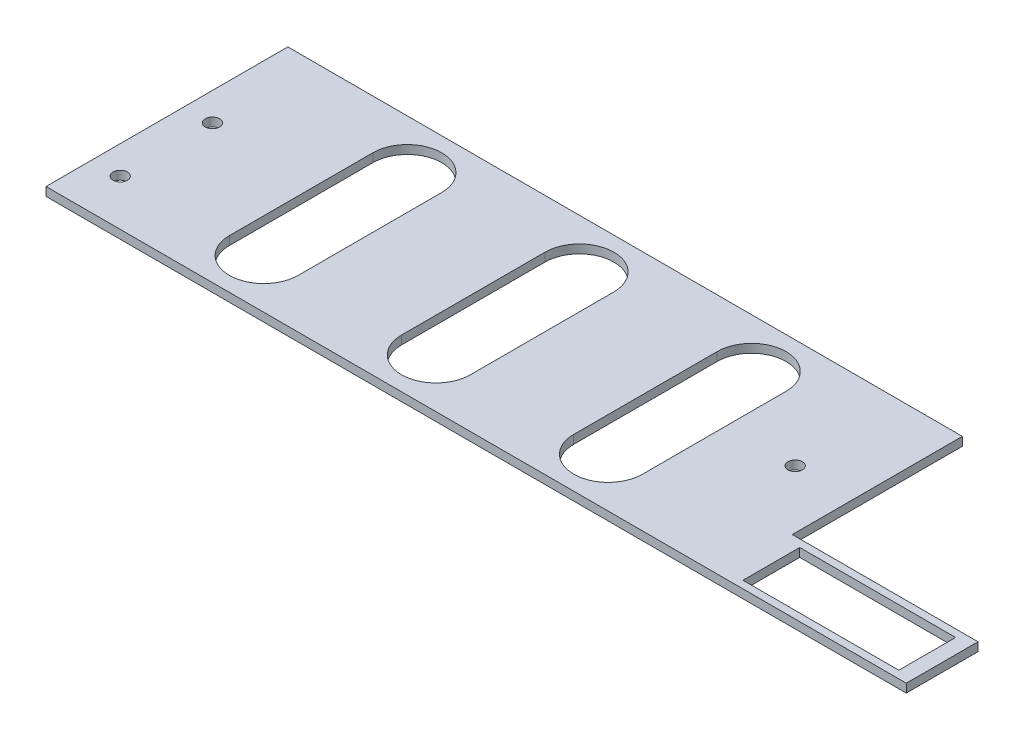
SolidWorks part; units mm, degrees
material "Custom Plastic"
ref_plane "Plan de face" through (0, 0, 0) normal (0, 0, 1) x (1, 0, 0)
ref_plane "Plan de dessus" through (0, 0, 0) normal (0, 1, 0) x (1, 0, 0)
ref_plane "Plan de droite" through (0, 0, 0) normal (1, 0, 0) x (0, 0, -1)
sketch "Esquisse1" plane through (0, 0, 0) normal (0, 1, 0) x (1, 0, 0)
  line L1 (-161.1743, 28.77) -> (138.6257, 28.77) construction
  line L2 (-161.1743, 28.77) -> (-161.1743, -35.5) construction
  line L3 (-161.1743, -35.5) -> (138.6257, -35.5) construction
  line L4 (138.6257, 28.77) -> (138.6257, -35.5) construction
  line L5 (-161.1743, 28.77) -> (138.6257, -35.5) construction
  line L6 (-161.1743, -35.5) -> (138.6257, 28.77) construction
  line L7 (138.6257, 18.77) -> (138.6257, -25.5) construction
  line L9 (-161.1743, 18.77) -> (-161.1743, -25.5)
  line L10 (-161.1743, 18.77) -> (-151.1743, 18.77) construction
  line L12 (-161.1743, -35.5) -> (138.6257, -35.5)
  line L13 (114.2615, -15.6877) -> (114.2615, -18.6342)
  line L14 (-151.1743, 28.77) -> (-151.1743, 18.77) construction
  line L15 (73.912, -0.4751) -> (73.912, -50000.4751) construction
  line L16 (-161.1743, -25.5) -> (-151.1743, -25.5) construction
  line L17 (-151.1743, -25.5) -> (-151.1743, -35.5) construction
  line L18 (67.162, 10.7475) -> (67.162, 2.8892) construction
  line L19 (-161.1743, 18.77) -> (138.6257, 18.77) construction
  line L20 (73.912, 28.77) -> (73.912, -10.5)
  line L21 (138.6257, -25.5) -> (-161.1743, -25.5) construction
  line L26 (114.2615, -15.6877) -> (79.1092, -15.6877)
  line L28 (-161.3743, 48.77) -> (-161.3743, -35.5) construction
  line L29 (114.2615, -15.6877) -> (114.2615, -32.887) construction
  line L30 (-161.1743, -25.5) -> (-161.1743, -35.5)
  line L33 (-161.1743, 28.77) -> (-161.1743, 18.77)
  line L34 (-161.1743, 28.77) -> (73.912, 28.77)
  line L36 (73.912, -10.5) -> (138.6257, -10.5)
  line L37 (138.6257, -10.5) -> (138.6257, -35.5)
  line L38 (114.2615, -32.887) -> (79.1092, -32.887)
  line L39 (138.6257, -35.5) -> (-161.3743, -35.5) construction
  line L40 (79.1092, -15.6877) -> (79.1092, -32.887)
  line L41 (114.2615, -15.6877) -> (79.1092, -32.887) construction
  line L42 (114.2615, -32.887) -> (79.1092, -15.6877) construction
  line L43 (-161.1743, -35.5) -> (-161.3743, -35.5) construction
  line L44 (132.6257, -18.6342) -> (114.2615, -18.6342)
  line L45 (132.6257, -18.6342) -> (132.6257, -32.887)
  line L46 (132.6257, -32.887) -> (114.2615, -32.887)
  line L47 (138.6257, -10.5) -> (73.912, -10.5) construction
  line L48 (114.2615, -18.6342) -> (114.2615, -32.887) construction
  line L49 (132.6257, -18.6342) -> (114.2615, -32.887) construction
  line L50 (73.912, 48.995) -> (73.912, -7.5) construction
  line L51 (132.6257, -32.887) -> (114.2615, -18.6342) construction
  circle A17 centre (-151.3743, -19.4325) radius 2.5
  circle A18 centre (-151.3743, 12.7025) radius 2.5
  circle A20 centre (-151.3743, 12.7025) radius 2.5 construction
  circle A21 centre (-151.3743, -19.4325) radius 2.5 construction
  circle A22 centre (53.662, 10.7475) radius 2.5
  point P4 (-11.2743, -3.365)
  point P45 (123.4436, -25.7606)
  point P56 (96.6853, -24.2874)
  dimension "D3" = 10
  dimension "D4" = 35.1524
  dimension "D5" = 6
  dimension "D7" = 5
  dimension "D2" = 18.3642
  dimension "D6" = 5
  dimension "D1" = 0.2
  dimension "D8" = 13.5
extrude "Boss.-Extru.1" add sketch "Esquisse1" along normal blind 3
sketch "Esquisse2" plane through (0, 0, 0) normal (0, -1, 0) x (1, 0, 0)
  line L0 (73.912, -28.77) -> (73.912, -38.77) construction
  line L1 (73.912, -38.77) -> (-43.6312, -38.77) construction
  line L2 (-43.6312, -38.77) -> (-161.1743, -38.77) construction
  line L3 (-161.1743, -38.77) -> (-161.1743, -28.77) construction
  line L4 (-155.8759, 3.365) -> (-167.4129, 3.365) construction
  line L5 (-161.1743, -28.77) -> (-161.1743, 35.5) construction
  line L6 (15.1404, -38.77) -> (15.1404, -50038.77) construction
  line L7 (-43.6312, -38.77) -> (-43.6312, -50038.77) construction
  line L8 (-102.4027, -38.77) -> (-102.4027, -50038.77) construction
  line L9 (7.6404, -11.635) -> (7.6404, 18.365)
  line L10 (22.6404, 18.365) -> (22.6404, -11.635)
  line L11 (22.6404, -11.635) -> (7.6404, -11.635) construction
  line L12 (7.6404, 18.365) -> (22.6404, 18.365) construction
  line L13 (22.6404, 3.365) -> (7.6404, 3.365) construction
  line L14 (-51.1312, -11.635) -> (-51.1312, 18.365)
  line L15 (-36.1312, 18.365) -> (-36.1312, -11.635)
  line L16 (-36.1312, -11.635) -> (-51.1312, -11.635) construction
  line L17 (-51.1312, 18.365) -> (-36.1312, 18.365) construction
  line L18 (-36.1312, 3.365) -> (-51.1312, 3.365) construction
  line L19 (-109.9027, -11.635) -> (-109.9027, 18.365)
  line L20 (-94.9027, 18.365) -> (-94.9027, -11.635)
  line L21 (-94.9027, -11.635) -> (-109.9027, -11.635) construction
  line L22 (-109.9027, 18.365) -> (-94.9027, 18.365) construction
  line L23 (-94.9027, 3.365) -> (-109.9027, 3.365) construction
  arc A0 (7.6404, -11.635) -> (22.6404, -11.635) centre (15.1404, -11.635) ccw
  arc A1 (7.6404, 18.365) -> (22.6404, 18.365) centre (15.1404, 18.365) cw
  arc A2 (-51.1312, -11.635) -> (-36.1312, -11.635) centre (-43.6312, -11.635) ccw
  arc A3 (-51.1312, 18.365) -> (-36.1312, 18.365) centre (-43.6312, 18.365) cw
  arc A4 (-109.9027, -11.635) -> (-94.9027, -11.635) centre (-102.4027, -11.635) ccw
  arc A5 (-109.9027, 18.365) -> (-94.9027, 18.365) centre (-102.4027, 18.365) cw
  point P8 (-161.1743, 3.365)
  point P10 (15.1404, -38.77)
  point P13 (-102.4027, -38.77)
  point P30 (15.1404, 3.365)
  point P41 (-43.6312, 3.365)
  point P51 (-102.4027, 3.365)
  dimension "D1" = 10
  dimension "D6" = 15
  dimension "D7" = 30
extrude "Enlèv. mat.-Extru.1" cut sketch "Esquisse2" against normal through all
sketch "Sketch1" plane through (0, 0, -28.77) normal (0, 0, -1) x (-1, 0, 0)
  line L1 (-73.912, 3) -> (161.1743, 3)
  line L2 (-73.912, 3) -> (-73.912, 0)
  line L3 (-73.912, 0) -> (161.1743, 0)
  line L4 (161.1743, 3) -> (161.1743, 0)
extrude "Boss-Extrude1" add sketch "Sketch1" along normal blind 20
sketch "Sketch2" plane through (0, 0, 0) normal (0, -1, 0) x (1, 0, 0)
  line L1 (79.1092, 32.887) -> (133.4257, 32.887)
  line L2 (79.1092, 32.887) -> (79.1092, 13.11)
  line L3 (79.1092, 13.11) -> (133.4257, 13.11)
  line L4 (133.4257, 32.887) -> (133.4257, 13.11)
  line L5 (138.6257, 10.5) -> (73.912, 10.5) construction
  line L7 (138.6257, 35.5) -> (138.6257, 10.5) construction
  dimension "D1" = 2.61
  dimension "D2" = 5.2
extrude "Cut-Extrude1" cut sketch "Sketch2" against normal blind 10
sketch "Sketch3" plane through (0, 0, 0) normal (0, -1, 0) x (-1, 0, 0)
  line L6 (102.4027, 39.135) -> (102.4027, -25.865) construction
  line L7 (102.4027, -18.365) -> (102.4027, 31.635) construction
  line L8 (90.4027, -18.365) -> (90.4027, 31.635)
  line L9 (114.4027, -18.365) -> (114.4027, 31.635)
  line L10 (42.4027, -18.365) -> (42.4027, 31.635) construction
  line L11 (30.4027, -18.365) -> (30.4027, 31.635)
  line L12 (54.4027, -18.365) -> (54.4027, 31.635)
  line L13 (-17.5973, -18.365) -> (-17.5973, 31.635) construction
  line L14 (-29.5973, -18.365) -> (-29.5973, 31.635)
  line L15 (-5.5973, -18.365) -> (-5.5973, 31.635)
  arc A0 (109.9027, -18.365) -> (94.9027, -18.365) centre (102.4027, -18.365) cw construction
  arc A1 (109.9027, 31.635) -> (94.9027, 31.635) centre (102.4027, 31.635) ccw construction
  arc A6 (90.4027, -18.365) -> (114.4027, -18.365) centre (102.4027, -18.365) ccw
  arc A7 (114.4027, 31.635) -> (90.4027, 31.635) centre (102.4027, 31.635) ccw
  arc A8 (30.4027, -18.365) -> (54.4027, -18.365) centre (42.4027, -18.365) ccw
  arc A9 (54.4027, 31.635) -> (30.4027, 31.635) centre (42.4027, 31.635) ccw
  arc A10 (-29.5973, -18.365) -> (-5.5973, -18.365) centre (-17.5973, -18.365) ccw
  arc A11 (-5.5973, 31.635) -> (-29.5973, 31.635) centre (-17.5973, 31.635) ccw
  point P14 (42.4027, 6.635)
  point P21 (-17.5973, 6.635)
  point P22 (102.4027, 6.635)
  dimension "D3" = 12
  dimension "D1" = 50
  dimension "D2" = 3
extrude "Cut-Extrude2" cut sketch "Sketch3" against normal blind 10
